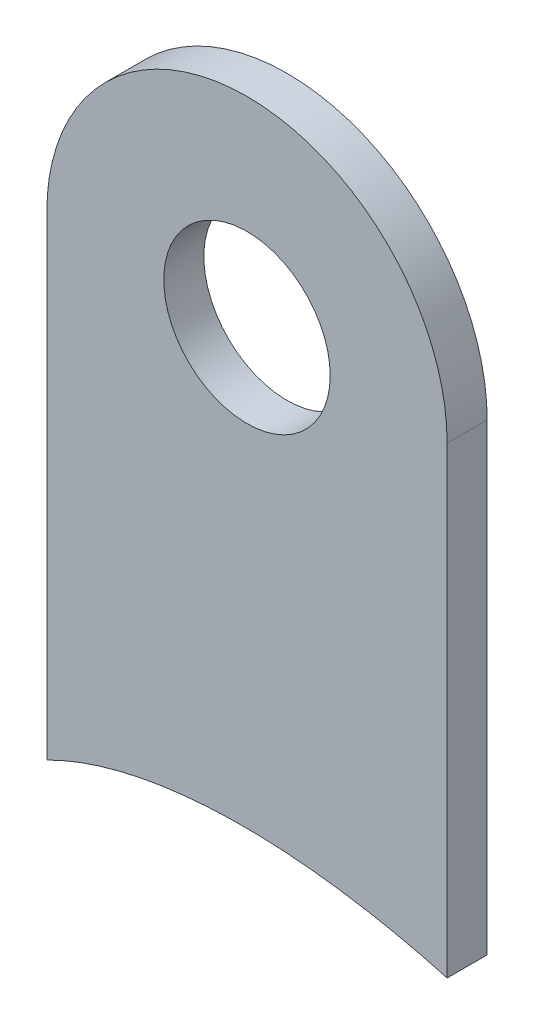
SolidWorks part; units mm, degrees
material "ASTM A36 Steel"
ref_plane "X-Y Datum" through (0, 0, 0) normal (0, 0, 1) x (1, 0, 0)
ref_plane "X-Z Datum" through (0, 0, 0) normal (0, 1, 0) x (1, 0, 0)
ref_plane "Y-Z Datum" through (0, 0, 0) normal (1, 0, 0) x (0, 0, -1)
sketch "Sketch1" plane through (0, 0, 0) normal (0, 0, 1) x (1, 0, 0)
  line L0 (-7.9375, 0) -> (-7.9375, -25.4)
  line L1 (-7.9375, -25.4) -> (7.9375, -25.4)
  line L2 (7.9375, -25.4) -> (7.9375, 0)
  circle A0 centre (0, 0) radius 7.9375
  circle A1 centre (0, 0) radius 3
  dimension "D1" = 6
  dimension "D2" = 15.875
  dimension "D3" = 25.4
extrude "Boss-Extrude1" add sketch "Sketch1" along normal blind 1.5875 contours A0 A1 | A0 L0 L1 L2 | A1
hole_wizard "M6 Clearance Hole1" positions "Sketch2" profile "Sketch3" hole size "M6" standard "ANSI Metric" end condition through all
sketch "Sketch2" plane through (0, 0, 1.5875) normal (0, 0, 1) x (1, 0, 0)
  point P0 (0, 0)
sketch "Sketch3" plane through (0, 0, 1.5875) normal (1, 0, 0) x (0, -1, 0)
  line L0 (0, 0) -> (0, 1.5875)
  line L1 (0, 1.5875) -> (3.3, 1.5875)
  line L2 (3.3, 1.5875) -> (3.3, 0)
  line L5 (3.3, 0) -> (0, 0)
  line L11 (0, -6.35) -> (0, 107.95) construction
  dimension "Thru Hole Dia." = 6.6
  dimension "Thru Hole Depth" = 1.5875
sketch "Sketch4" [suppressed] plane through (0, 0, 2.54) normal (0, 0, 1) x (1, 0, 0)
  line L1 (57.1174, 89.0913) -> (2.6108, -25.4)
  line L3 (1.0953, -29.3967) -> (-107.8628, 152.3221)
  line M3 (-7.9375, 0) -> (-7.9375, -25.4)
  line M4 (-7.9375, -25.4) -> (7.9375, -25.4)
  line M5 (7.9375, -25.4) -> (7.9375, 0)
extrude "Cut-Extrude1" [suppressed] cut sketch "Sketch4" against normal through all contours L3 M4 M3 | L1 M5 M4
sketch "Sketch5" plane through (0, 0, 1.5875) normal (0, 0, 1) x (1, 0, 0)
  line L0 (-7.9375, 0) -> (-7.9375, -25.4) construction
  line L1 (7.9375, -25.4) -> (-7.9375, -25.4)
  line L2 (7.9375, -25.4) -> (7.9375, -19.05)
  line L3 (7.9375, -19.05) -> (-7.9375, -19.05)
  line L4 (-7.9375, -25.4) -> (-7.9375, -19.05)
  dimension "D1" = 6.35
extrude "Cut-Extrude2" cut sketch "Sketch5" against normal through all
sketch "Sketch6" plane through (0, 0, 0) normal (0, 0, -1) x (-1, 0, 0)
  spline S0 degree 3 poles (12.0303, -22.8994) (1.6525, 0.2838) (-38.2843, -17.5937) (-27.9064, -40.7769) (-17.5286, -63.9601) (22.4081, -46.0826) (12.0303, -22.8994) (1.6525, 0.2838) (-38.2843, -17.5937) knots -0.5 0 0 0 0.5 0.5 0.5 1 1 1 1.5 1.5 1.5 weights 1 0.333333 0.333333 1 0.333333 0.333333 1 0.333333 0.333333 only from (12.0303, -22.8994) to (12.0303, -22.8994)
  spline S1 degree 3 poles (12.0303, -22.8994) (1.6525, 0.2838) (-38.2843, -17.5937) (-27.9064, -40.7769) (-17.5286, -63.9601) (22.4081, -46.0826) (12.0303, -22.8994) (1.6525, 0.2838) (-38.2843, -17.5937) knots -0.5 0 0 0 0.5 0.5 0.5 1 1 1 1.5 1.5 1.5 weights 1 0.333333 0.333333 1 0.333333 0.333333 1 0.333333 0.333333 only from (12.0303, -22.8994) to (12.0303, -22.8994)
extrude "Cut-Extrude3" cut sketch "Sketch6" against normal through all
